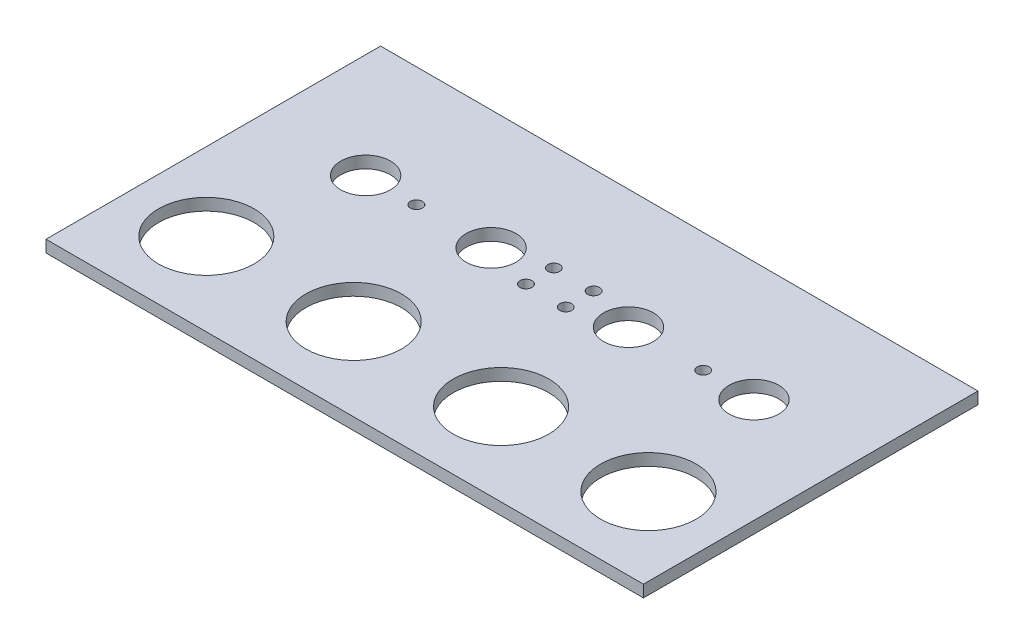
SolidWorks part; units mm, degrees
ref_plane "Front Plane" through (0, 0, 0) normal (0, 0, 1) x (1, 0, 0)
ref_plane "Top Plane" through (0, 0, 0) normal (0, 1, 0) x (1, 0, 0)
ref_plane "Right Plane" through (0, 0, 0) normal (1, 0, 0) x (0, 0, -1)
sketch "Sketch1" plane through (0, 0, 0) normal (0, 1, 0) x (1, 0, 0)
  line L0 (-60.5687, 15.2866) -> (89.4313, 15.2866) construction
  line L5 (-60.5687, 45.2866) -> (89.4313, 45.2866)
  line L6 (-60.5687, 45.2866) -> (-60.5687, -38.7134)
  line L7 (-60.5687, -38.7134) -> (89.4313, -38.7134)
  line L8 (89.4313, 45.2866) -> (89.4313, -38.7134)
  line L9 (-60.5687, -17.9634) -> (89.4313, -17.9634) construction
  line L10 (14.4313, 45.2866) -> (14.4313, -38.7134) construction
  line L11 (9.4313, 45.2866) -> (9.4313, -38.7134) construction
  circle A0 centre (-41.0687, -17.9634) radius 12
  circle A1 centre (-4.0687, -17.9634) radius 12
  circle A2 centre (-34.3187, 15.2866) radius 6.25
  circle A3 centre (-21.5687, 15.2866) radius 1.5
  circle A4 centre (-2.8187, 15.2866) radius 6.25
  circle A5 centre (9.4313, 18.7866) radius 1.5
  circle A6 centre (9.4313, 11.7866) radius 1.5
  circle A7 centre (69.9313, -17.9634) radius 12
  circle A8 centre (32.9313, -17.9634) radius 12
  circle A9 centre (19.4313, 11.7866) radius 1.5
  circle A10 centre (19.4313, 18.7866) radius 1.5
  circle A11 centre (31.6813, 15.2866) radius 6.25
  circle A12 centre (50.4313, 15.2866) radius 1.5
  circle A13 centre (63.1813, 15.2866) radius 6.25
  point P26 (13.8336, 45.2866)
  dimension "D5" = 19.5
  dimension "D6" = 26.25
  dimension "D8" = 12.5
  dimension "D9" = 39
  dimension "D10" = 57.75
  dimension "D13" = 3
  dimension "D15" = 3
  dimension "D1" = 150
  dimension "D2" = 84
  dimension "D3" = 30
  dimension "D4" = 20.75
  dimension "D7" = 56.5
  dimension "D11" = 5
  dimension "D12" = 26.5
  dimension "D14" = 33.5
extrude "Boss-Extrude2" add sketch "Sketch1" against normal blind 3 contours L6 L5 L8 L7
